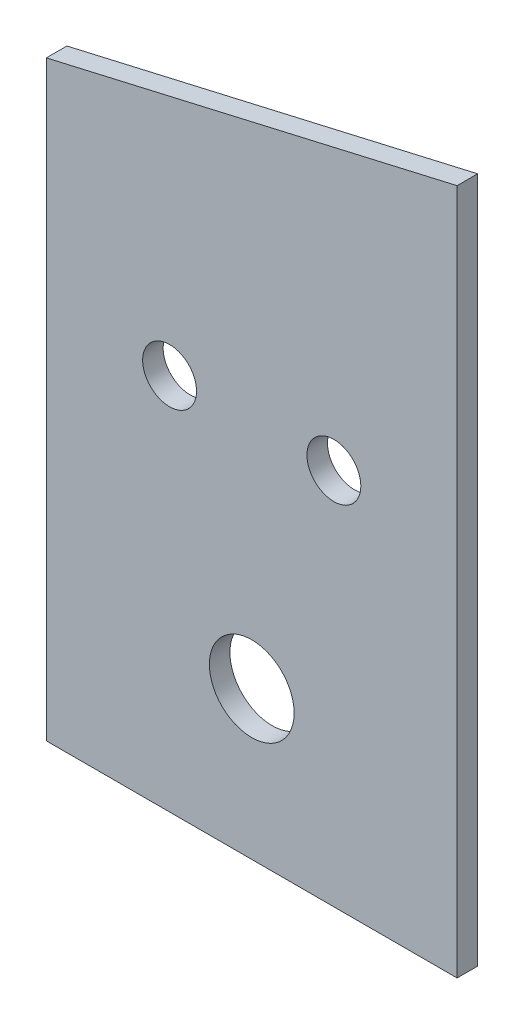
SolidWorks part; units mm, degrees
ref_plane "Front Plane" through (0, 0, 0) normal (0, 0, 1) x (1, 0, 0)
ref_plane "Top Plane" through (0, 0, 0) normal (0, 1, 0) x (1, 0, 0)
ref_plane "Right Plane" through (0, 0, 0) normal (1, 0, 0) x (0, 0, -1)
sketch "Sketch2" plane through (0, 0, 0) normal (0, 0, 1) x (1, 0, 0)
  line L0 (0, 35.56) -> (31.75, 35.56)
  line L1 (0, 0) -> (31.75, 0)
  line L2 (0, 0) -> (0, 45.72)
  line L3 (0, 45.72) -> (31.75, 45.72)
  line L4 (31.75, 0) -> (31.75, 45.72)
  line L5 (0, 22.86) -> (31.75, 22.86)
  line L6 (0, 45.72) -> (31.75, 53.041)
  line L7 (31.75, 53.041) -> (31.75, 45.72)
  circle A0 centre (9.525, 29.21) radius 2.0828
  circle A1 centre (22.225, 29.21) radius 2.0828
  circle A2 centre (15.875, 11.43) radius 3.2766
  point P14 (15.875, 45.72)
  dimension "D4" = 4.1656
  dimension "D5" = 10.16
  dimension "D11" = 6.5532
  dimension "D9" = 12.7
  dimension "D1" = 45.72
  dimension "D2" = 31.75
  dimension "D3" = 11.43
  dimension "D6" = 9.525
  dimension "D7" = 9.525
  dimension "D8" = 16.51
  dimension "D10" = 12.984
extrude "Boss-Extrude1" add sketch "Sketch2" along normal blind 1.5875
